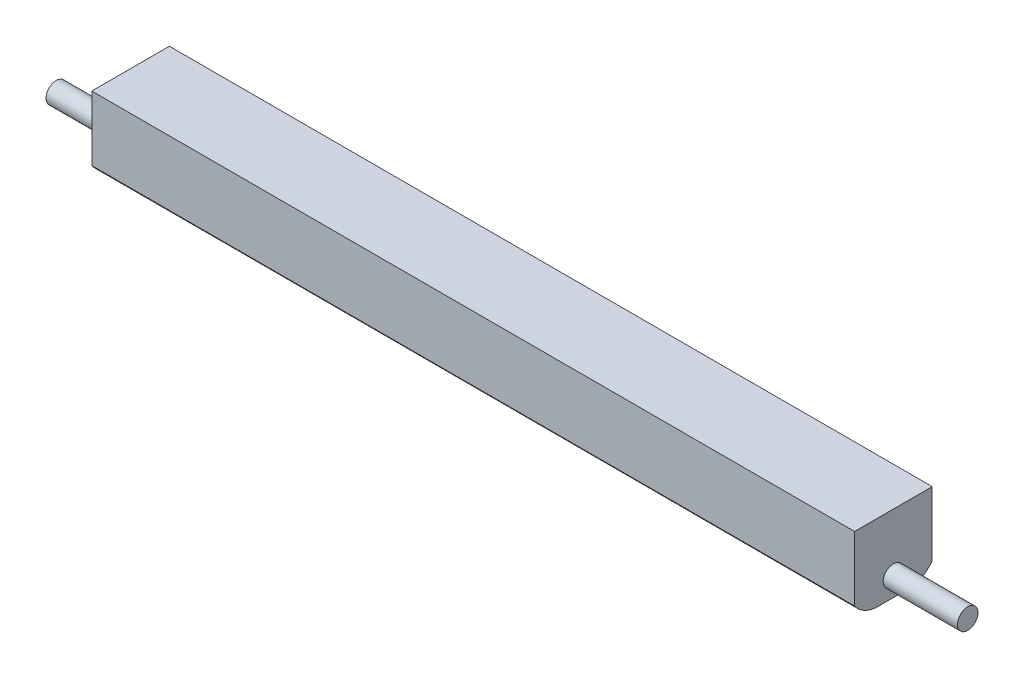
SolidWorks part; units mm, degrees
ref_plane "Front Plane" through (0, 0, 0) normal (0, 0, 1) x (1, 0, 0)
ref_plane "Top Plane" through (0, 0, 0) normal (0, 1, 0) x (1, 0, 0)
ref_plane "Right Plane" through (0, 0, 0) normal (1, 0, 0) x (0, 0, -1)
sketch "Sketch2" plane through (0, 0, 0) normal (1, 0, 0) x (0, 0, -1)
  line L0 (-47.6601, 39.5561) -> (47.6601, 39.5561)
  line L1 (47.6601, 39.5561) -> (47.6601, -16.7593)
  line L2 (24.8618, -39.5561) -> (-25.1199, -39.5561)
  line L3 (-47.6601, 39.5561) -> (-47.6601, -16.7593)
  line L4 (0, 70.0653) -> (0, -97.4839) construction
  circle A0 centre (0, 0) radius 25
  arc A1 (-47.6601, -16.7593) -> (-25.1199, -39.5561) centre (-24.8618, -16.7593) ccw
  arc A2 (24.8618, -39.5561) -> (47.6601, -16.7593) centre (24.8618, -16.7579) ccw
  dimension "D2" = 22.7982
  dimension "D3" = 22.7982
  dimension "D5" = 50
  dimension "D1" = 79.1122
  dimension "D4" = 56.3154
sketch "Sketch3" plane through (0, 0, 0) normal (0, 0, 1) x (1, 0, 0)
  line L0 (0, 187.4459) -> (0, -139.3035) construction
  line L1 (-621.1777, 124.9892) -> (621.1777, 124.9892)
  line L2 (-621.1777, 124.9892) -> (-621.1777, -97.9082)
  line L3 (-621.1777, -97.9082) -> (621.1777, -97.9082)
  line L4 (621.1777, 124.9892) -> (621.1777, -97.9082)
ref_plane "Plane1" through (238.76, 0, 0) normal (1, 0, 0) x (0, 0, -1)
sketch "Sketch4" plane through (238.76, 0, 0) normal (1, 0, 0) x (0, 0, -1)
  line L13 (-38.3839, -46.3817) -> (35.7004, -46.3817)
  line L14 (94.6345, 142.6029) -> (94.6345, -16.7593)
  line L15 (-94.6345, 142.6029) -> (94.6345, 142.6029)
  line L16 (-94.6345, 142.6029) -> (-94.6345, -16.7593)
  arc A7 (-94.6345, -16.7593) -> (-38.3839, -46.3817) centre (-37.5682, 23.3862) ccw
  arc A8 (94.6345, -16.7593) -> (35.7004, -46.3817) centre (37.555, 23.3648) cw
ref_plane "Plane3" through (0, 0, 0) normal (1, 0, 0) x (0, 0, -1)
sketch "Sketch11" plane through (0, 0, 0) normal (1, 0, 0) x (0, 0, -1)
  line L0 (-94.6345, 140.6183) -> (-94.6345, -16.7593)
  line L1 (-94.6345, 140.6183) -> (94.6345, 140.6183)
  line L2 (94.6345, 140.6183) -> (94.6345, -16.7593)
  line L3 (-38.3839, -46.3817) -> (35.7004, -46.3817)
  line L5 (-94.6345, -16.7593) -> (-84.7964, -31.6852) construction
  line L6 (-84.7964, -31.6852) -> (-69.209, -41.5439) construction
  line L7 (-69.209, -41.5439) -> (-51.629, -46.9662) construction
  line L8 (-51.629, -46.9662) -> (-38.3839, -46.3817) construction
  arc A0 (35.7004, -46.3817) -> (94.6345, -16.7593) centre (37.555, 23.3648) ccw construction
  spline S0 degree 4 poles (-94.6345, -16.7593) (-84.7964, -31.6852) (-69.209, -41.5439) (-51.629, -46.9662) (-38.3839, -46.3817) knots 0 0 0 0 0 1 1 1 1 1
  spline S1 degree 2 poles (94.6345, -16.7593) (68.0889, -47.7008) (35.7004, -46.3817) knots 0 0 0 0.879182 0.879182 0.879182
  dimension "D1" = 187
extrude "Boss-Extrude1" add sketch "Sketch11" along normal mid plane 1860 contours L1 L2 S1 L3 S0 L0
extrude "Boss-Extrude2" add sketch "Sketch2" along normal mid plane 2222.5 separate body contours A0
